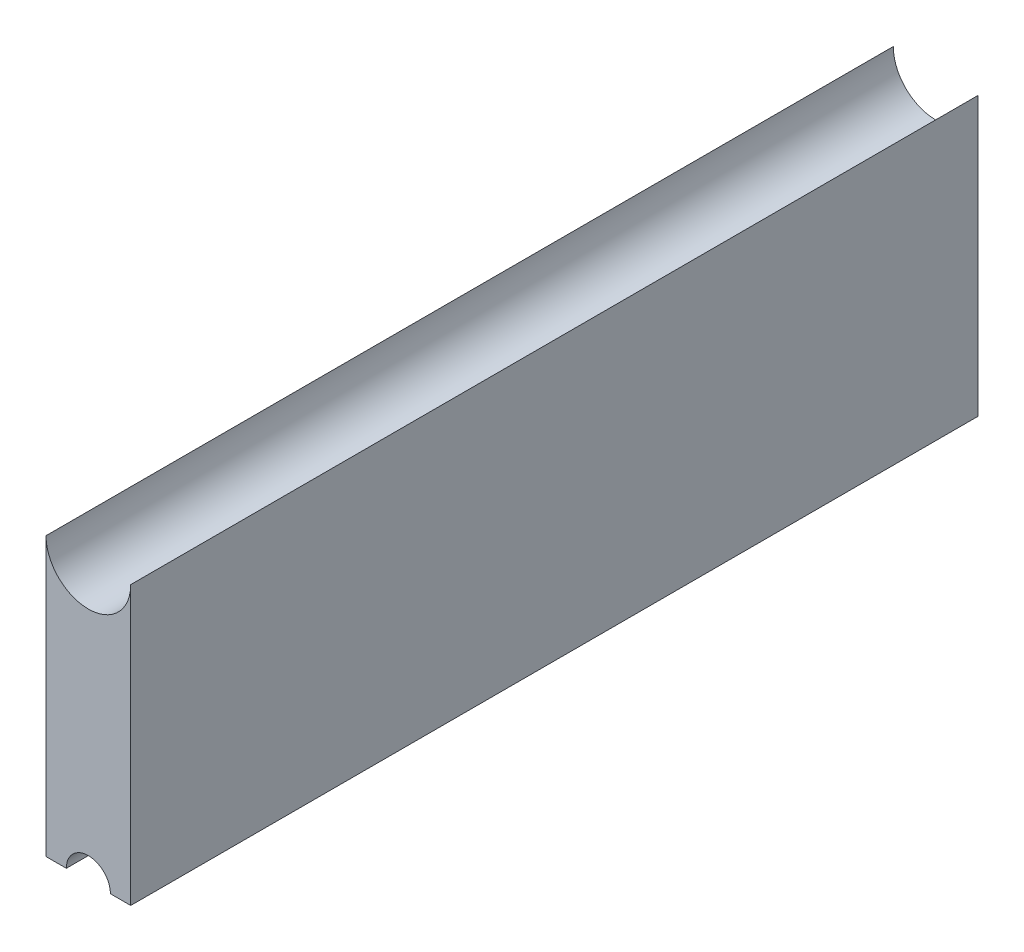
SolidWorks part; units mm, degrees
ref_plane "Front Plane" through (0, 0, 0) normal (0, 0, 1) x (1, 0, 0)
ref_plane "Top Plane" through (0, 0, 0) normal (0, 1, 0) x (1, 0, 0)
ref_plane "Right Plane" through (0, 0, 0) normal (1, 0, 0) x (0, 0, -1)
sketch "Sketch1" plane through (0, 0, 0) normal (0, 0, 1) x (1, 0, 0)
  line L16 (-5.207, -8.382) -> (-11.557, -8.382)
  line L17 (-5.207, -8.382) -> (-5.207, -29.21)
  line L18 (-11.557, -8.382) -> (-11.557, -29.21)
  line L19 (-5.207, -29.21) -> (-11.557, -29.21)
  circle A0 centre (-8.382, -8.382) radius 3.175
  circle A1 centre (-8.382, -29.21) radius 1.651
  dimension "D9" = 6.35
  dimension "D10" = 3.302
  dimension "D2" = 20.828
  dimension "D11" = 20.828
extrude "Boss-Extrude4" add sketch "Sketch1" along normal blind 63.5 contours A1 L19 L17 A0 L18
